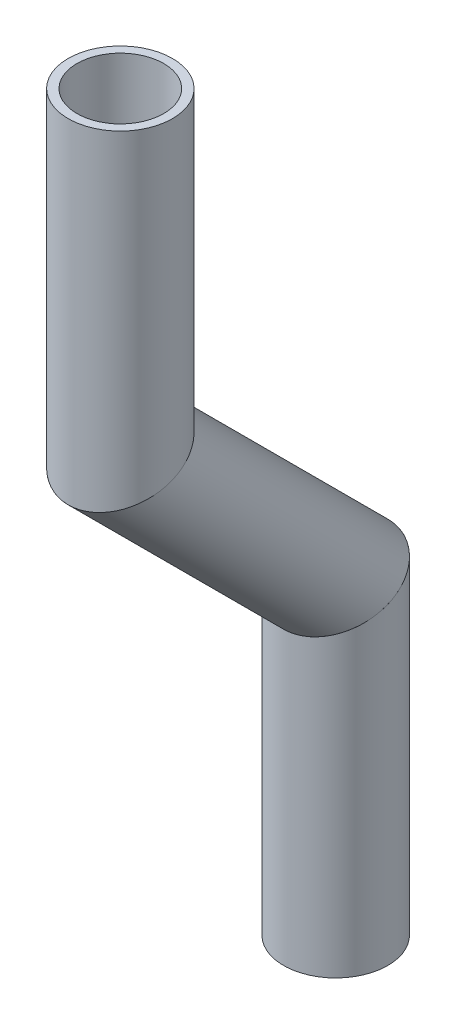
SolidWorks part; units mm, degrees
ref_plane "Front Plane" through (0, 0, 0) normal (0, 0, 1) x (1, 0, 0)
ref_plane "Top Plane" through (0, 0, 0) normal (0, 1, 0) x (1, 0, 0)
ref_plane "Right Plane" through (0, 0, 0) normal (1, 0, 0) x (0, 0, -1)
sketch "Sketch1" plane through (0, 0, 0) normal (1, 0, 0) x (0, 0, -1)
  line L0 (-300.5313, -210.6016) -> (-300.5313, -248.7016)
  line L1 (-300.5313, -248.7016) -> (-274.3047, -274.9281)
  line L2 (-274.3047, -274.9281) -> (-274.3047, -313.0281)
  line L3 (-300.5313, -248.7016) -> (-300.5313, -238.7774) construction
  dimension "D1" = 45
  dimension "D2" = 38.1
  dimension "D3" = 38.1
other "Pipe 0.5 SCH 40(1)"
ref_plane "Plane1" through (0, -210.6016, 300.5313) normal (0, -1, 0) x (0, 0, -1)
sketch "Sketch11" plane through (0, -210.6016, 300.5313) normal (0, -1, 0) x (0, 0, -1)
  circle A0 centre (0, 0) radius 5.2832
  circle A1 centre (0, 0) radius 6.35
  point P5 (0, 0)
  dimension "In_dia" = 10.5664
  dimension "Out_dia" = 12.7
